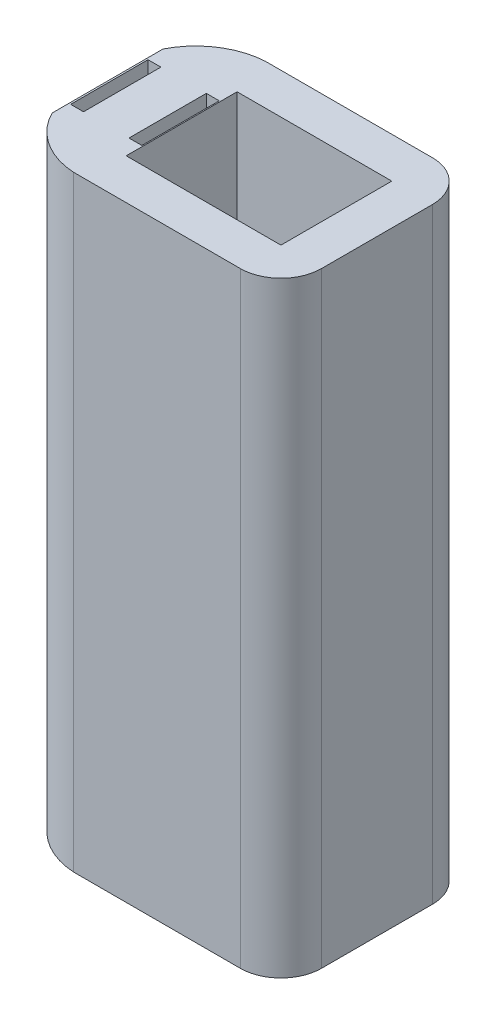
SolidWorks part; units mm, degrees
ref_plane "Front Plane" through (0, 0, 0) normal (0, 0, 1) x (1, 0, 0)
ref_plane "Top Plane" through (0, 0, 0) normal (0, 1, 0) x (1, 0, 0)
ref_plane "Right Plane" through (0, 0, 0) normal (1, 0, 0) x (0, 0, -1)
sketch "Sketch1" plane through (0, 0, 0) normal (0, 1, 0) x (1, 0, 0)
  line L1 (60, -43) -> (-60, -43)
  line L2 (60, -43) -> (60, 43)
  line L3 (60, 43) -> (-60, 43)
  line L4 (-60, -43) -> (-60, 43)
  line L5 (60, -43) -> (-60, 43) construction
  line L6 (60, 43) -> (-60, -43) construction
  line L10 (60, 74.46) -> (-69.3776, 74.46)
  line L12 (60, -74.46) -> (-69.3776, -74.46)
  line L13 (91.46, -43) -> (91.46, 43)
  line L14 (-91.46, -74.46) -> (-91.46, 74.46) construction
  line L15 (91.46, -74.46) -> (-91.46, -74.46) construction
  line L16 (91.46, -74.46) -> (91.46, 74.46) construction
  line L17 (91.46, 74.46) -> (-91.46, 74.46) construction
  line L18 (-117.46, -43) -> (-117.46, 43)
  line L20 (-70.86, 30.0204) -> (-60.86, 30.0204)
  line L21 (-70.86, 30.0204) -> (-70.86, -29.9796)
  line L22 (-70.86, -29.9796) -> (-60.86, -29.9796)
  line L23 (-60.86, 30.0204) -> (-60.86, -29.9796)
  line L24 (-116.1, 30.0204) -> (-106.1, 30.0204)
  line L25 (-116.1, 30.0204) -> (-116.1, -29.9796)
  line L26 (-116.1, -29.9796) -> (-106.1, -29.9796)
  line L27 (-106.1, 30.0204) -> (-106.1, -29.9796)
  arc A9 (60, -74.46) -> (91.46, -43) centre (60, -43) ccw
  arc A10 (60, 74.46) -> (91.46, 43) centre (60, 43) cw
  arc A11 (-117.46, 43) -> (-69.3776, 74.46) centre (-66.1736, 17.0894) cw
  arc A12 (-117.46, -43) -> (-69.3776, -74.46) centre (-66.1736, -17.0894) ccw
  point P0 (0, 0)
  dimension "D7" = 13.008
  dimension "D8" = 10
  dimension "D9" = 0.86
  dimension "D4" = 31.46
  dimension "D12" = 57.46
  dimension "D13" = 57.46
  dimension "D1" = 120
  dimension "D2" = 86
  dimension "D6" = 60
  dimension "D10" = 10
  dimension "D11" = 60
  dimension "D14" = 57.46
  dimension "D15" = 57.46
  dimension "D16" = 0
  dimension "D17" = 106.1
  dimension "D5" = 1.36
  dimension "D3" = 31.46
extrude "Boss-Extrude1" add sketch "Sketch1" along normal blind 470
